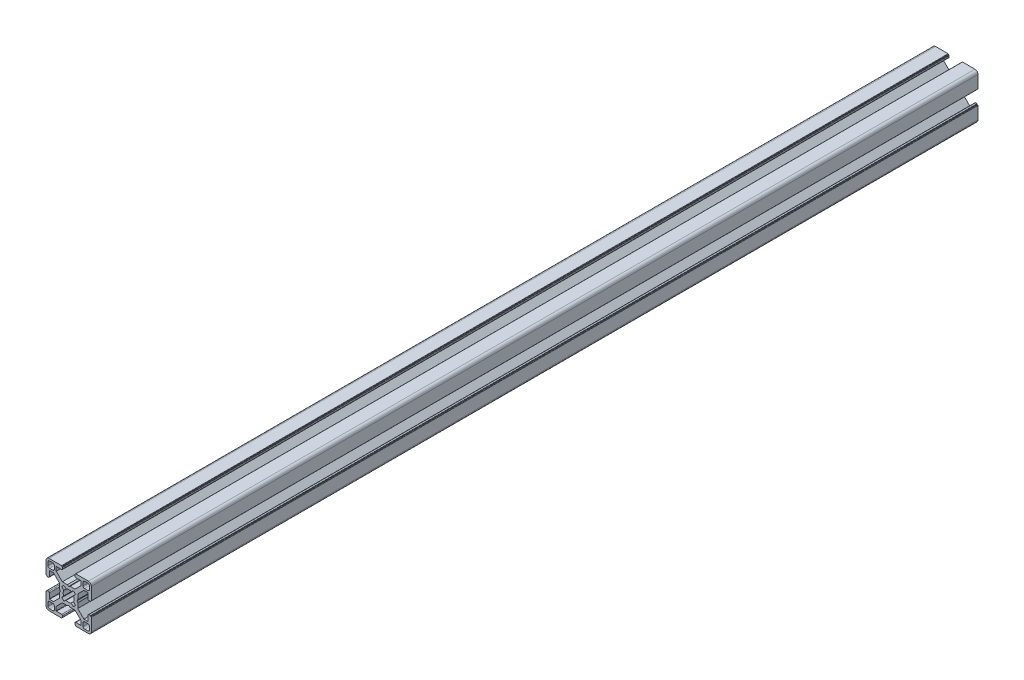
SolidWorks part; units mm, degrees
material "6061 Alloy"
ref_plane "Front" through (0, 0, 0) normal (0, 0, 1) x (1, 0, 0)
ref_plane "Top" through (0, 0, 0) normal (0, 1, 0) x (1, 0, 0)
ref_plane "Right" through (0, 0, 0) normal (1, 0, 0) x (0, 0, -1)
sketch "Sketch1" plane through (0, 0, 0) normal (0, 0, 1) x (1, 0, 0)
  line L0 (13.7, 12.7) -> (13.7, 10.5)
  line L1 (10.5, 9.5) -> (12.7, 9.5)
  line L2 (9.5, 12.7) -> (9.5, 10.5)
  line L3 (10.5, 13.7) -> (12.7, 13.7)
  line L4 (3.1359, 4.5184) -> (1.6001, 3.2806)
  line L5 (3.2806, 1.6001) -> (4.5053, 3.1547)
  line L6 (6.0045, 0.9) -> (5.4849, 0)
  line L7 (6.0045, 4.2045) -> (6.0045, 0.9)
  line L8 (0, -5.4849) -> (0.9, -6)
  line L9 (0.9, -6) -> (4.2045, -6)
  line L10 (4.2045, -6) -> (8.25, -10.05)
  line L11 (8.25, -10.05) -> (8.25, -12.6)
  line L12 (4.65, -12.8) -> (8.05, -12.8)
  line L13 (4.05, -14.3) -> (4.05, -13.4)
  line L14 (4.25, -14.5) -> (4.35, -14.5)
  line L15 (4.55, -14.8) -> (4.55, -14.7)
  line L16 (4.75, -15) -> (13, -15)
  line L17 (15, -13) -> (15, -4.75)
  line L18 (14.7, -4.55) -> (14.8, -4.55)
  line L19 (14.5, -4.35) -> (14.5, -4.25)
  line L20 (13.4, -4.05) -> (14.3, -4.05)
  line L21 (12.8, -8.05) -> (12.8, -4.65)
  line L22 (12.6, -8.25) -> (10.05, -8.25)
  line L23 (10.05, -8.25) -> (6.0045, -4.2045)
  line L24 (6.0045, -4.2045) -> (6.0045, -0.9)
  line L25 (6.0045, -0.9) -> (5.4849, 0)
  line L26 (10.05, 8.25) -> (6.0045, 4.2045)
  line L27 (12.6, 8.25) -> (10.05, 8.25)
  line L28 (12.8, 8.05) -> (12.8, 4.65)
  line L29 (13.4, 4.05) -> (14.3, 4.05)
  line L30 (14.5, 4.35) -> (14.5, 4.25)
  line L31 (14.7, 4.55) -> (14.8, 4.55)
  line L32 (15, 13) -> (15, 4.75)
  line L33 (4.75, 15) -> (13, 15)
  line L34 (4.55, 14.8) -> (4.55, 14.7)
  line L35 (4.25, 14.5) -> (4.35, 14.5)
  line L36 (4.05, 14.3) -> (4.05, 13.4)
  line L37 (4.65, 12.8) -> (8.05, 12.8)
  line L38 (8.25, 10.05) -> (8.25, 12.6)
  line L39 (4.2045, 6) -> (8.25, 10.05)
  line L40 (0.9, 6) -> (4.2045, 6)
  line L41 (0, 5.4849) -> (0.9, 6)
  line L42 (-13.7, -12.7) -> (-13.7, -10.5)
  line L43 (-10.5, -9.5) -> (-12.7, -9.5)
  line L44 (-9.5, -12.7) -> (-9.5, -10.5)
  line L45 (-10.5, -13.7) -> (-12.7, -13.7)
  line L46 (-3.1359, -4.5184) -> (-1.6001, -3.2806)
  line L47 (-3.2806, -1.6001) -> (-4.5053, -3.1547)
  line L48 (0, 5.4849) -> (-0.9, 6)
  line L49 (-0.9, 6) -> (-4.2045, 6)
  line L50 (-4.2045, 6) -> (-8.25, 10.05)
  line L51 (-8.25, 10.05) -> (-8.25, 12.6)
  line L52 (-4.65, 12.8) -> (-8.05, 12.8)
  line L53 (-4.05, 14.3) -> (-4.05, 13.4)
  line L54 (-4.25, 14.5) -> (-4.35, 14.5)
  line L55 (-4.55, 14.8) -> (-4.55, 14.7)
  line L56 (-4.75, 15) -> (-13, 15)
  line L57 (-15, 13) -> (-15, 4.75)
  line L58 (-14.7, 4.55) -> (-14.8, 4.55)
  line L59 (-14.5, 4.35) -> (-14.5, 4.25)
  line L60 (-13.4, 4.05) -> (-14.3, 4.05)
  line L61 (-12.8, 8.05) -> (-12.8, 4.65)
  line L62 (-12.6, 8.25) -> (-10.05, 8.25)
  line L63 (-10.05, 8.25) -> (-6.0045, 4.2045)
  line L64 (-6.0045, -0.9) -> (-5.4849, 0)
  line L65 (-6.0045, -4.2045) -> (-6.0045, -0.9)
  line L66 (-10.05, -8.25) -> (-6.0045, -4.2045)
  line L67 (-12.6, -8.25) -> (-10.05, -8.25)
  line L68 (-12.8, -8.05) -> (-12.8, -4.65)
  line L69 (-13.4, -4.05) -> (-14.3, -4.05)
  line L70 (-14.5, -4.35) -> (-14.5, -4.25)
  line L71 (-14.7, -4.55) -> (-14.8, -4.55)
  line L72 (-15, -13) -> (-15, -4.75)
  line L73 (-4.75, -15) -> (-13, -15)
  line L74 (-4.55, -14.8) -> (-4.55, -14.7)
  line L75 (-4.25, -14.5) -> (-4.35, -14.5)
  line L76 (-4.05, -14.3) -> (-4.05, -13.4)
  line L77 (3.2806, -1.6001) -> (4.5053, -3.1547)
  line L78 (3.1359, -4.5184) -> (1.6001, -3.2806)
  line L79 (-4.65, -12.8) -> (-8.05, -12.8)
  line L80 (-8.25, -10.05) -> (-8.25, -12.6)
  line L81 (-4.2045, -6) -> (-8.25, -10.05)
  line L82 (-0.9, -6) -> (-4.2045, -6)
  line L83 (0, -5.4849) -> (-0.9, -6)
  line L84 (10.5, -13.7) -> (12.7, -13.7)
  line L85 (9.5, -12.7) -> (9.5, -10.5)
  line L86 (10.5, -9.5) -> (12.7, -9.5)
  line L87 (13.7, -12.7) -> (13.7, -10.5)
  line L88 (-6.0045, 4.2045) -> (-6.0045, 0.9)
  line L89 (-6.0045, 0.9) -> (-5.4849, 0)
  line L90 (-3.2806, 1.6001) -> (-4.5053, 3.1547)
  line L91 (-3.1359, 4.5184) -> (-1.6001, 3.2806)
  line L92 (-10.5, 13.7) -> (-12.7, 13.7)
  line L93 (-9.5, 12.7) -> (-9.5, 10.5)
  line L94 (-10.5, 9.5) -> (-12.7, 9.5)
  line L95 (-13.7, 12.7) -> (-13.7, 10.5)
  line L96 (-23.4857, 0) -> (20.9308, 0) construction
  line L97 (0, 17.9563) -> (0, -17.361) construction
  arc A0 (13.7, 12.7) -> (12.7, 13.7) centre (12.7, 12.7) ccw
  arc A1 (12.7, 9.5) -> (13.7, 10.5) centre (12.7, 10.5) ccw
  arc A2 (9.5, 10.5) -> (10.5, 9.5) centre (10.5, 10.5) ccw
  arc A3 (10.5, 13.7) -> (9.5, 12.7) centre (10.5, 12.7) ccw
  arc A4 (1.6001, 3.2806) -> (-1.6001, 3.2806) centre (0, 0) ccw
  arc A5 (8.25, -12.6) -> (8.05, -12.8) centre (8.05, -12.6) cw
  arc A6 (4.65, -12.8) -> (4.05, -13.4) centre (4.65, -13.4) ccw
  arc A7 (4.05, -14.3) -> (4.25, -14.5) centre (4.25, -14.3) ccw
  arc A8 (4.35, -14.5) -> (4.55, -14.7) centre (4.35, -14.7) cw
  arc A9 (4.55, -14.8) -> (4.75, -15) centre (4.75, -14.8) ccw
  arc A10 (13, -15) -> (15, -13) centre (13, -13) ccw
  arc A11 (15, -4.75) -> (14.8, -4.55) centre (14.8, -4.75) ccw
  arc A12 (14.7, -4.55) -> (14.5, -4.35) centre (14.7, -4.35) cw
  arc A13 (14.5, -4.25) -> (14.3, -4.05) centre (14.3, -4.25) ccw
  arc A14 (13.4, -4.05) -> (12.8, -4.65) centre (13.4, -4.65) ccw
  arc A15 (12.8, -8.05) -> (12.6, -8.25) centre (12.6, -8.05) cw
  arc A16 (4.5053, 3.1547) -> (3.1359, 4.5184) centre (0, 0) ccw
  arc A17 (12.8, 8.05) -> (12.6, 8.25) centre (12.6, 8.05) ccw
  arc A18 (13.4, 4.05) -> (12.8, 4.65) centre (13.4, 4.65) cw
  arc A19 (14.5, 4.25) -> (14.3, 4.05) centre (14.3, 4.25) cw
  arc A20 (14.7, 4.55) -> (14.5, 4.35) centre (14.7, 4.35) ccw
  arc A21 (15, 4.75) -> (14.8, 4.55) centre (14.8, 4.75) cw
  arc A22 (13, 15) -> (15, 13) centre (13, 13) cw
  arc A23 (4.55, 14.8) -> (4.75, 15) centre (4.75, 14.8) cw
  arc A24 (4.35, 14.5) -> (4.55, 14.7) centre (4.35, 14.7) ccw
  arc A25 (4.05, 14.3) -> (4.25, 14.5) centre (4.25, 14.3) cw
  arc A26 (4.65, 12.8) -> (4.05, 13.4) centre (4.65, 13.4) cw
  arc A27 (8.25, 12.6) -> (8.05, 12.8) centre (8.05, 12.6) ccw
  arc A28 (-13.7, -12.7) -> (-12.7, -13.7) centre (-12.7, -12.7) ccw
  arc A29 (-12.7, -9.5) -> (-13.7, -10.5) centre (-12.7, -10.5) ccw
  arc A30 (-9.5, -10.5) -> (-10.5, -9.5) centre (-10.5, -10.5) ccw
  arc A31 (-10.5, -13.7) -> (-9.5, -12.7) centre (-10.5, -12.7) ccw
  arc A32 (-4.5053, -3.1547) -> (-3.1359, -4.5184) centre (0, 0) ccw
  arc A33 (-3.2806, 1.6001) -> (-3.2806, -1.6001) centre (0, 0) ccw
  arc A34 (-8.25, 12.6) -> (-8.05, 12.8) centre (-8.05, 12.6) cw
  arc A35 (-4.65, 12.8) -> (-4.05, 13.4) centre (-4.65, 13.4) ccw
  arc A36 (-4.05, 14.3) -> (-4.25, 14.5) centre (-4.25, 14.3) ccw
  arc A37 (-4.35, 14.5) -> (-4.55, 14.7) centre (-4.35, 14.7) cw
  arc A38 (-4.55, 14.8) -> (-4.75, 15) centre (-4.75, 14.8) ccw
  arc A39 (-13, 15) -> (-15, 13) centre (-13, 13) ccw
  arc A40 (-15, 4.75) -> (-14.8, 4.55) centre (-14.8, 4.75) ccw
  arc A41 (-14.7, 4.55) -> (-14.5, 4.35) centre (-14.7, 4.35) cw
  arc A42 (-14.5, 4.25) -> (-14.3, 4.05) centre (-14.3, 4.25) ccw
  arc A43 (-13.4, 4.05) -> (-12.8, 4.65) centre (-13.4, 4.65) ccw
  arc A44 (-12.8, 8.05) -> (-12.6, 8.25) centre (-12.6, 8.05) cw
  arc A45 (-4.5053, 3.1547) -> (-3.1359, 4.5184) centre (0, 0) cw
  arc A46 (-12.8, -8.05) -> (-12.6, -8.25) centre (-12.6, -8.05) ccw
  arc A47 (-13.4, -4.05) -> (-12.8, -4.65) centre (-13.4, -4.65) cw
  arc A48 (-14.5, -4.25) -> (-14.3, -4.05) centre (-14.3, -4.25) cw
  arc A49 (3.2806, 1.6001) -> (3.2806, -1.6001) centre (0, 0) cw
  arc A50 (4.5053, -3.1547) -> (3.1359, -4.5184) centre (0, 0) cw
  arc A51 (1.6001, -3.2806) -> (-1.6001, -3.2806) centre (0, 0) cw
  arc A52 (-14.7, -4.55) -> (-14.5, -4.35) centre (-14.7, -4.35) ccw
  arc A53 (-15, -4.75) -> (-14.8, -4.55) centre (-14.8, -4.75) cw
  arc A54 (-13, -15) -> (-15, -13) centre (-13, -13) cw
  arc A55 (-4.55, -14.8) -> (-4.75, -15) centre (-4.75, -14.8) cw
  arc A56 (10.5, -13.7) -> (9.5, -12.7) centre (10.5, -12.7) cw
  arc A57 (9.5, -10.5) -> (10.5, -9.5) centre (10.5, -10.5) cw
  arc A58 (12.7, -9.5) -> (13.7, -10.5) centre (12.7, -10.5) cw
  arc A59 (13.7, -12.7) -> (12.7, -13.7) centre (12.7, -12.7) cw
  arc A60 (-4.35, -14.5) -> (-4.55, -14.7) centre (-4.35, -14.7) ccw
  arc A61 (-4.05, -14.3) -> (-4.25, -14.5) centre (-4.25, -14.3) cw
  arc A62 (-4.65, -12.8) -> (-4.05, -13.4) centre (-4.65, -13.4) cw
  arc A63 (-8.25, -12.6) -> (-8.05, -12.8) centre (-8.05, -12.6) ccw
  arc A64 (-10.5, 13.7) -> (-9.5, 12.7) centre (-10.5, 12.7) cw
  arc A65 (-9.5, 10.5) -> (-10.5, 9.5) centre (-10.5, 10.5) cw
  arc A66 (-12.7, 9.5) -> (-13.7, 10.5) centre (-12.7, 10.5) cw
  arc A67 (-13.7, 12.7) -> (-12.7, 13.7) centre (-12.7, 12.7) cw
  point P81 (15, 15)
  point P82 (0, 15)
  point P203 (0, -15)
  point P204 (15, -15)
  point P206 (0, 0)
  point P207 (15, 0)
  point P219 (-15, 0)
  point P220 (-15, -15)
  point P221 (-15, 15)
  dimension "D6" = 7.3
  dimension "D7" = 11
  dimension "D1" = 30
  dimension "D2" = 15
  dimension "D3" = 30
  dimension "D4" = 8.1
  dimension "D5" = 9
  dimension "D8" = 8.1
extrude "Boss-Extrude1" add sketch "Sketch1" along normal blind 586.105
